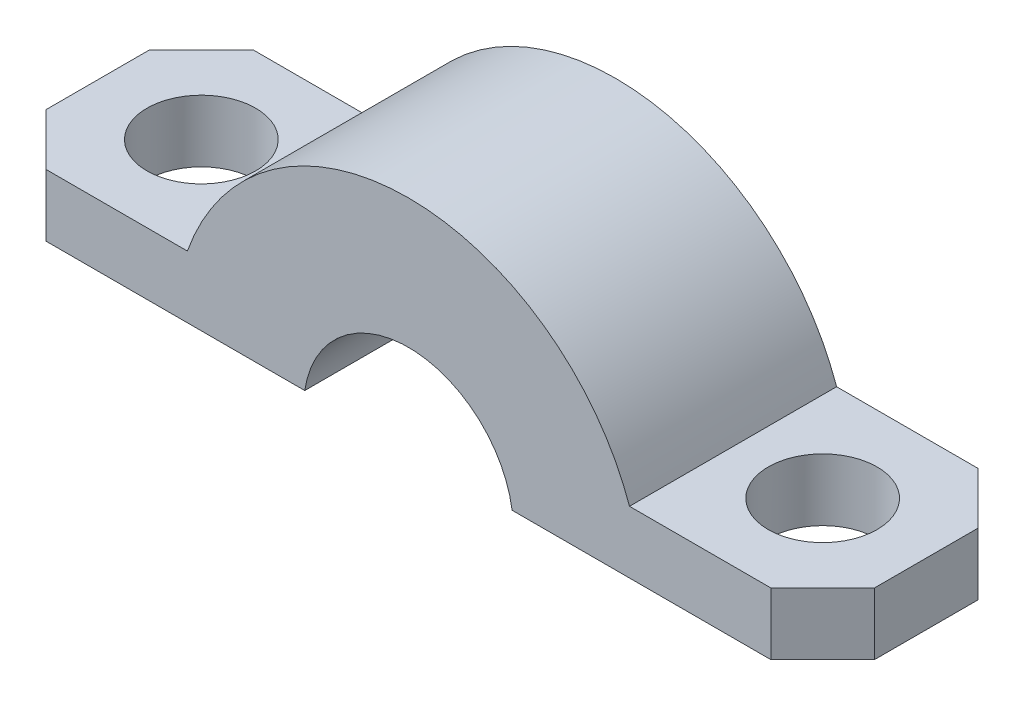
SolidWorks part; units mm, degrees
ref_plane "Front Plane" through (0, 0, 0) normal (0, 0, 1) x (1, 0, 0)
ref_plane "Top Plane" through (0, 0, 0) normal (0, 1, 0) x (1, 0, 0)
ref_plane "Right Plane" through (0, 0, 0) normal (1, 0, 0) x (0, 0, -1)
sketch "Sketch1" plane through (0, 0, 0) normal (0, 0, 1) x (1, 0, 0)
  line L0 (-4.05, 0) -> (-16, 0)
  line L1 (-16, 0) -> (-16, 3)
  line L2 (-16, 3) -> (-8.5383, 3)
  line L3 (8.5383, 3) -> (16, 3)
  line L4 (16, 3) -> (16, 0)
  line L5 (16, 0) -> (4.05, 0)
  line L6 (-8.5383, 3) -> (8.5383, 3) construction
  line L7 (0, 3) -> (0, 0) construction
  arc A0 (-4.05, 0) -> (4.05, 0) centre (0, 0) cw
  arc A1 (-8.5383, 3) -> (8.5383, 3) centre (0, 0) cw
  dimension "D1" = 4.05
  dimension "D2" = 5
  dimension "D3" = 32
  dimension "D4" = 3
extrude "Boss-Extrude1" add sketch "Sketch1" along normal mid plane 8
sketch "Sketch2" plane through (0, 0, 0) normal (0, 1, 0) x (1, 0, 0)
  line L0 (0, 0) -> (-12, 0) construction
  line L1 (0, 0) -> (12, 0) construction
  circle A0 centre (-12, 0) radius 2.1
  circle A1 centre (12, 0) radius 2.1
  dimension "D2" = 4.2
  dimension "D1" = 24
extrude "Cut-Extrude1" cut sketch "Sketch2" along normal through all
sketch "Sketch3" plane through (0, 0, 0) normal (0, 1, 0) x (1, 0, 0)
  line L1 (20, -5) -> (-20, -5)
  line L2 (20, -5) -> (20, 5)
  line L3 (20, 5) -> (-20, 5)
  line L4 (-20, -5) -> (-20, 5)
  line L5 (20, -5) -> (-20, 5) construction
  line L6 (20, 5) -> (-20, -5) construction
  point P0 (0, 0)
  dimension "D1" = 10
  dimension "D2" = 40
extrude "Cut-Extrude2" cut sketch "Sketch3" along normal blind 0.6
chamfer "Chamfer1" distance 2 angle 45 4 edges at (16, 1.8, -4) (16, 1.8, 4) (-16, 1.8, -4) (-16, 1.8, 4)
